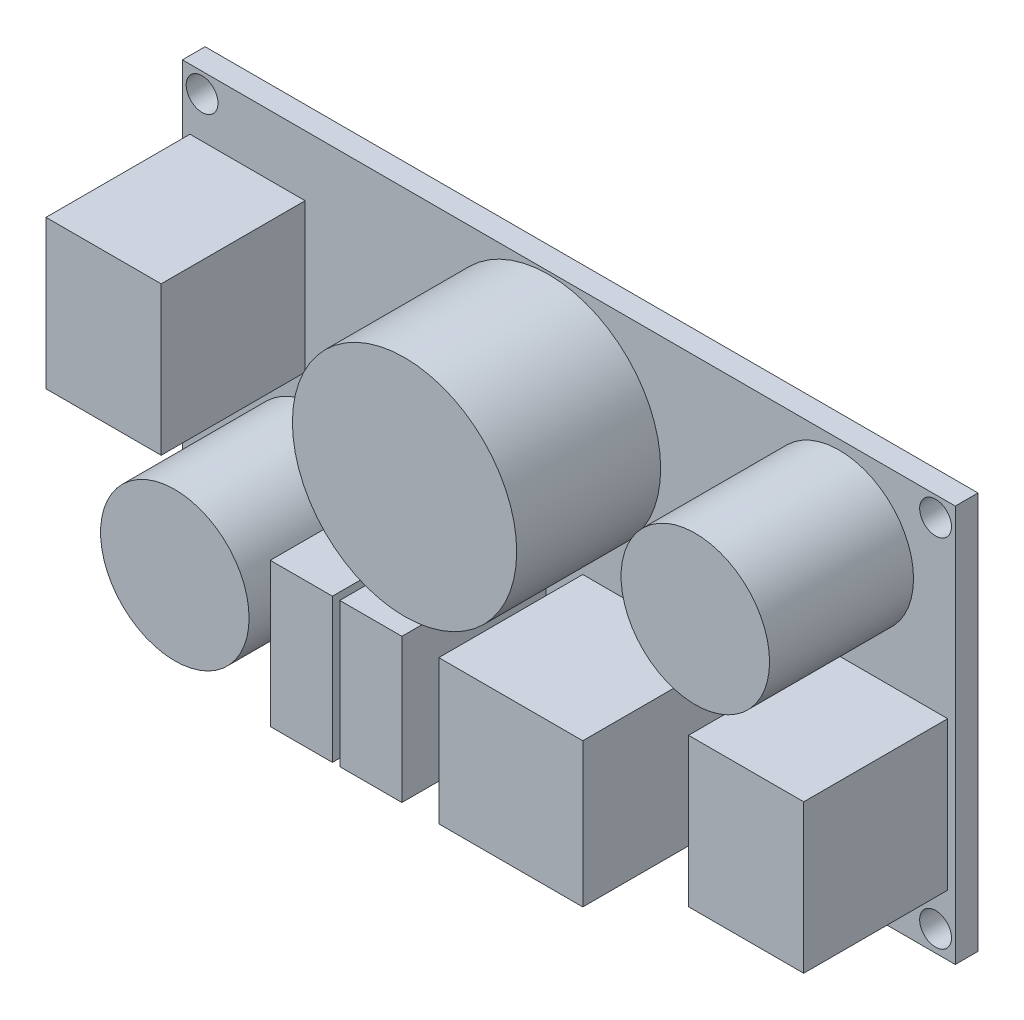
SolidWorks part; units mm, degrees
ref_plane "Спереди" through (0, 0, 0) normal (0, 0, 1) x (1, 0, 0)
ref_plane "Сверху" through (0, 0, 0) normal (0, 1, 0) x (1, 0, 0)
ref_plane "Справа" through (0, 0, 0) normal (1, 0, 0) x (0, 0, -1)
sketch "Эскиз1" plane through (0, 0, 0) normal (0, 0, 1) x (1, 0, 0)
  line L1 (-25.5, 13.1) -> (25.5, 13.1)
  line L2 (-25.5, 13.1) -> (-25.5, -13.1)
  line L3 (-25.5, -13.1) -> (25.5, -13.1)
  line L4 (25.5, 13.1) -> (25.5, -13.1)
  line L5 (-25.5, 13.1) -> (25.5, -13.1) construction
  line L6 (-25.5, -13.1) -> (25.5, 13.1) construction
  point P0 (0, 0)
  dimension "D1" = 26.2
  dimension "D2" = 51
extrude "Бобышка-Вытянуть1" add sketch "Эскиз1" along normal blind 1.5
sketch "Эскиз2" plane through (0, 0, 1.5) normal (0, 0, 1) x (1, 0, 0)
  line L0 (25.5, 13.1) -> (-25.5, 13.1) construction
  line L1 (-25, 9.1) -> (-17.4, 9.1)
  line L2 (-25, 9.1) -> (-25, -0.7)
  line L3 (-25, -0.7) -> (-17.4, -0.7)
  line L4 (-17.4, 9.1) -> (-17.4, -0.7)
  line L5 (-25, 9.1) -> (-17.4, -0.7) construction
  line L6 (-25, -0.7) -> (-17.4, 9.1) construction
  line L7 (17.4, 0.7) -> (25, 0.7)
  line L8 (17.4, 0.7) -> (17.4, -9.1)
  line L9 (17.4, -9.1) -> (25, -9.1)
  line L10 (25, 0.7) -> (25, -9.1)
  line L11 (17.4, 0.7) -> (25, -9.1) construction
  line L12 (17.4, -9.1) -> (25, 0.7) construction
  line L13 (-10.2, -3.1) -> (-6.1, -3.1)
  line L14 (-10.2, -3.1) -> (-10.2, -12.6)
  line L15 (-10.2, -12.6) -> (-6.1, -12.6)
  line L16 (-6.1, -3.1) -> (-6.1, -12.6)
  line L17 (-10.2, -3.1) -> (-6.1, -12.6) construction
  line L18 (-10.2, -12.6) -> (-6.1, -3.1) construction
  line L19 (-5.6156, -3.1) -> (-1.5156, -3.1)
  line L20 (-5.6156, -3.1) -> (-5.6156, -12.6)
  line L21 (-5.6156, -12.6) -> (-1.5156, -12.6)
  line L22 (-1.5156, -3.1) -> (-1.5156, -12.6)
  line L23 (-5.6156, -3.1) -> (-1.5156, -12.6) construction
  line L24 (-5.6156, -12.6) -> (-1.5156, -3.1) construction
  line L25 (0.9199, -3.1013) -> (10.4199, -3.1013)
  line L26 (0.9199, -3.1013) -> (0.9199, -12.6013)
  line L27 (0.9199, -12.6013) -> (10.4199, -12.6013)
  line L28 (10.4199, -3.1013) -> (10.4199, -12.6013)
  line L29 (0.9199, -3.1013) -> (10.4199, -12.6013) construction
  line L30 (0.9199, -12.6013) -> (10.4199, -3.1013) construction
  line L31 (-25.5, 13.1) -> (-25.5, -13.1) construction
  line L33 (-25.5, -13.1) -> (25.5, -13.1) construction
  line L34 (25.5, -13.1) -> (25.5, 13.1) construction
  circle A0 centre (17.8455, 7.5692) radius 4.9
  circle A1 centre (-1.3404, 5.5192) radius 7.4
  circle A2 centre (-16.5, -7.1) radius 4.9
  point P0 (-21.2, 4.2)
  point P5 (21.2, -4.2)
  point P10 (-8.15, -7.85)
  point P15 (-3.5656, -7.85)
  point P24 (5.6699, -7.8513)
  point P40 (-3.5656, -12.6)
  dimension "D9" = 9.5
  dimension "D11" = 4
  dimension "D13" = 9.8
  dimension "D14" = 9.8
  dimension "D15" = 14.8
  dimension "D1" = 9.8
  dimension "D2" = 7.6
  dimension "D3" = 4
  dimension "D4" = 0.5
  dimension "D5" = 9.5
  dimension "D6" = 4.1
  dimension "D7" = 9.5
  dimension "D8" = 4.1
  dimension "D10" = 9.5
  dimension "D12" = 0.5
  dimension "D16" = 9
  dimension "D17" = 6
  dimension "D18" = 15.3
  dimension "D19" = 0.5
  dimension "D20" = 0.5
extrude "Бобышка-Вытянуть2" add sketch "Эскиз2" along normal blind 9.5
sketch "Эскиз3" plane through (0, 0, 1.5) normal (0, 0, 1) x (1, 0, 0)
  circle A0 centre (-24.2002, 11.7929) radius 1.05
  circle A1 centre (24.1998, 11.7929) radius 1.05
  circle A2 centre (24.1998, -11.7071) radius 1.05
  circle A3 centre (-24.2002, -11.7071) radius 1.05
  dimension "D1" = 2.1
  dimension "D2" = 2
  dimension "D3" = 2
extrude "Вырез-Вытянуть2" cut sketch "Эскиз3" against normal through all
